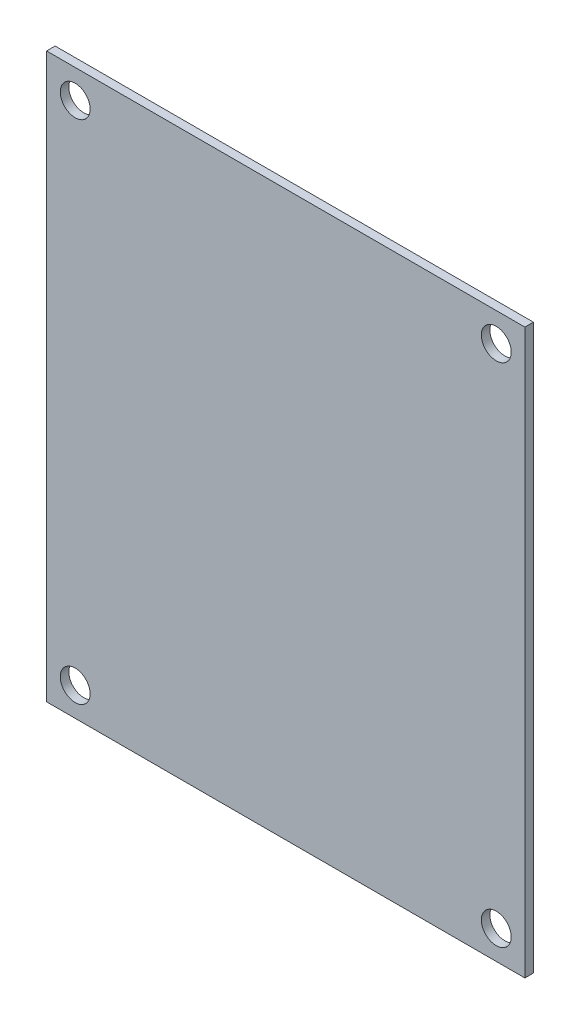
SolidWorks part; units mm, degrees
ref_plane "Front Plane" through (0, 0, 0) normal (0, 0, 1) x (1, 0, 0)
ref_plane "Top Plane" through (0, 0, 0) normal (0, 1, 0) x (1, 0, 0)
ref_plane "Right Plane" through (0, 0, 0) normal (1, 0, 0) x (0, 0, -1)
sketch "Sketch1" plane through (0, 0, 0) normal (0, 0, 1) x (1, 0, 0)
  line L0 (-24.65, 29.65) -> (-24.65, -29.65) construction
  line L1 (-28, 33) -> (28, 33)
  line L2 (-28, 33) -> (-28, -33)
  line L3 (-28, -33) -> (28, -33)
  line L4 (28, 33) -> (28, -33)
  line L5 (-28, 33) -> (28, -33) construction
  line L6 (-28, -33) -> (28, 33) construction
  line L7 (-24.65, -29.65) -> (24.65, -29.65) construction
  line L8 (24.65, -29.65) -> (24.65, 29.65) construction
  line L9 (24.65, 29.65) -> (-24.65, 29.65) construction
  line L10 (0, 29.65) -> (0, -29.65) construction
  circle A0 centre (-24.65, 29.65) radius 1.75
  circle A1 centre (24.65, 29.65) radius 1.75
  circle A2 centre (24.65, -29.65) radius 1.75
  circle A3 centre (-24.65, -29.65) radius 1.75
  point P0 (0, 0)
  point P17 (0, 0)
  dimension "D1" = 3.5
  dimension "D2" = 56
  dimension "D3" = 66
  dimension "D4" = 3.35
  dimension "D5" = 3.35
extrude "Boss-Extrude1" add sketch "Sketch1" along normal blind 1
